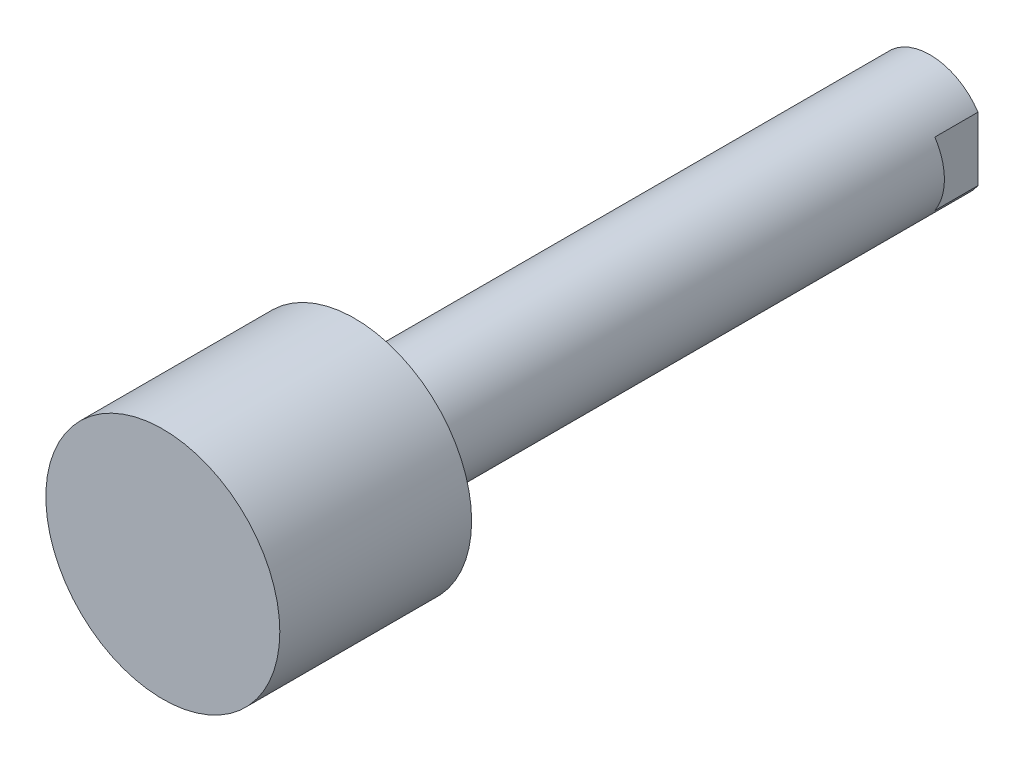
SolidWorks part; units mm, degrees
ref_plane "Front Plane" through (0, 0, 0) normal (0, 0, 1) x (1, 0, 0)
ref_plane "Top Plane" through (0, 0, 0) normal (0, 1, 0) x (1, 0, 0)
ref_plane "Right Plane" through (0, 0, 0) normal (1, 0, 0) x (0, 0, -1)
sketch "Sketch1" plane through (0, 0, 0) normal (0, 0, 1) x (1, 0, 0)
  circle A0 centre (0, 0) radius 3
  dimension "D1" = 6
extrude "Boss-Extrude1" add sketch "Sketch1" along normal blind 30
sketch "Sketch2" plane through (0, 0, 30) normal (0, 0, 1) x (1, 0, 0)
  circle A0 centre (0, 0) radius 6.0996
extrude "Boss-Extrude2" add sketch "Sketch2" along normal blind 10
sketch "Sketch3" plane through (0, 0, 0) normal (0, 1, 0) x (1, 0, 0)
  line L0 (3, 0) -> (-3, 0) construction
  line L1 (4.9338, -2.25) -> (2.5, -2.25)
  line L2 (4.9338, -2.25) -> (4.9338, 0)
  line L3 (4.9338, 0) -> (2.5, 0)
  line L4 (2.5, -2.25) -> (2.5, 0)
  line L5 (-5.2042, -2.25) -> (-2.5, -2.25)
  line L6 (-5.2042, -2.25) -> (-5.2042, 0)
  line L7 (-5.2042, 0) -> (-2.5, 0)
  line L8 (-2.5, -2.25) -> (-2.5, 0)
  line L9 (0, 0) -> (0, -5.138) construction
  dimension "D1" = 2.25
  dimension "D2" = 5
extrude "Cut-Extrude1" cut sketch "Sketch3" against normal through all and the other way through all
hole_wizard "Tap Drill for M3x0.5 Tap1" positions "Sketch5" profile "Sketch4" hole size "M3x0.5" standard "ANSI Metric"
sketch "Sketch5" plane through (0, 0, 0) normal (0, 0, -1) x (-1, 0, 0)
  point P0 (0, 0)
sketch "Sketch4" plane through (0, 0, 0) normal (1, 0, 0) x (0, 1, 0)
  line L0 (0, 0) -> (0, 3.7511)
  line L1 (0, 3.7511) -> (1.25, 3)
  line L2 (1.25, 3) -> (1.25, 0)
  line L5 (1.25, 0) -> (0, 0)
  line L10 (0, 3.7511) -> (-1.25, 3) construction
  line L11 (0, -6.35) -> (0, 107.95) construction
  dimension "Hole Dia." = 2.5
  dimension "Hole Depth" = 3
  dimension "Drill Angle" = 118
